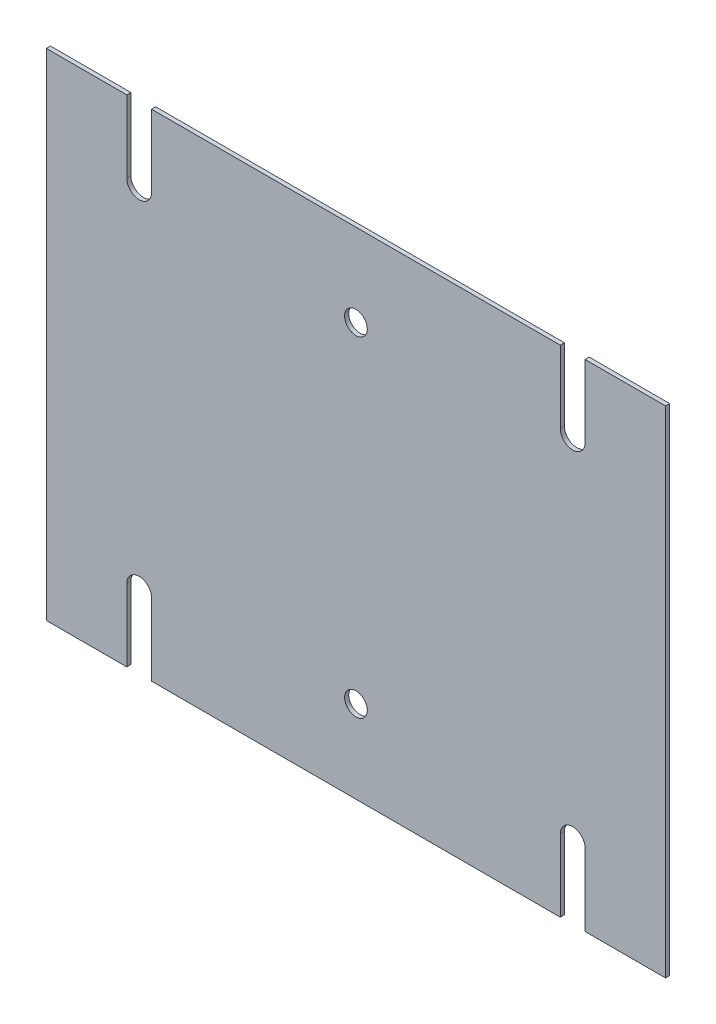
SolidWorks part; units mm, degrees
material "Galvanized Steel"
ref_plane "Front Plane" through (0, 0, 0) normal (0, 0, 1) x (1, 0, 0)
ref_plane "Top Plane" through (0, 0, 0) normal (0, 1, 0) x (1, 0, 0)
ref_plane "Right Plane" through (0, 0, 0) normal (1, 0, 0) x (0, 0, -1)
sketch "Sketch1" plane through (0, 0, 0) normal (0, 0, 1) x (1, 0, 0)
  line L0 (68.9488, -26.6338) -> (98.9488, -26.6338)
  line L1 (68.9488, 58.3662) -> (29.9488, 58.3662)
  line L2 (68.9488, 58.3662) -> (68.9488, -26.6338)
  line L3 (68.9488, -181.6338) -> (29.9488, -181.6338)
  line L4 (-231.0512, 58.3662) -> (-231.0512, -30.1799)
  line L5 (98.9488, -26.6338) -> (98.9488, -96.6338)
  line L6 (98.9488, -96.6338) -> (68.9488, -96.6338)
  line L7 (-231.0512, -30.1799) -> (-261.0512, -30.1799)
  line L8 (-261.0512, -30.1799) -> (-261.0512, -100.1799)
  line L9 (-261.0512, -100.1799) -> (-231.0512, -100.1799)
  line L10 (-231.0512, -100.1799) -> (-231.0512, -181.6338)
  line L11 (68.9488, -96.6338) -> (68.9488, -181.6338)
  line L12 (17.9488, -181.6338) -> (-180.0512, -181.6338)
  line L13 (-180.0512, 58.3662) -> (-180.0512, 23.3662)
  line L14 (-192.0512, 58.3662) -> (-192.0512, 23.3662)
  line L16 (-192.0512, -181.6338) -> (-192.0512, -146.6338)
  line L17 (-180.0512, -181.6338) -> (-180.0512, -146.6338)
  line L18 (-192.0512, -181.6338) -> (-231.0512, -181.6338)
  line L19 (29.9488, -146.6338) -> (29.9488, -181.6338)
  line L20 (17.9488, -146.6338) -> (17.9488, -181.6338)
  line L21 (-192.0512, 58.3662) -> (-231.0512, 58.3662)
  line L22 (29.9488, 58.3662) -> (29.9488, 23.3662)
  line L23 (17.9488, 58.3662) -> (17.9488, 23.3662)
  line L24 (17.9488, 58.3662) -> (-180.0512, 58.3662)
  circle A0 centre (-81.0512, -141.6338) radius 5.5
  arc A1 (-192.0512, 23.3662) -> (-180.0512, 23.3662) centre (-186.0512, 23.3662) ccw
  circle A2 centre (-81.0512, 18.3662) radius 5.5
  arc A3 (-180.0512, -146.6338) -> (-192.0512, -146.6338) centre (-186.0512, -146.6338) ccw
  arc A4 (29.9488, -146.6338) -> (17.9488, -146.6338) centre (23.9488, -146.6338) ccw
  circle A5 centre (83.9488, -61.6338) radius 3.25
  circle A6 centre (-246.0512, -65.1799) radius 3.25
  arc A7 (17.9488, 23.3662) -> (29.9488, 23.3662) centre (23.9488, 23.3662) ccw
  point P14 (-186.0512, 50.7838)
  point P21 (-186.0512, -182.4408)
  point P26 (23.9488, -182.4408)
  point P33 (23.9488, 50.7838)
  dimension "D18" = 11
  dimension "D19" = 11
  dimension "D20" = 6.5
  dimension "D21" = 6.5
  dimension "D26" = 11
  dimension "D27" = 6.5
  dimension "D1" = 240
  dimension "D2" = 300
  dimension "D3" = 30
  dimension "D4" = 70
  dimension "D5" = 45
  dimension "D6" = 30
  dimension "D7" = 70
  dimension "D8" = 12
  dimension "D9" = 12
  dimension "D10" = 39
  dimension "D11" = 39
  dimension "D12" = 12
  dimension "D13" = 12
  dimension "D14" = 35
  dimension "D15" = 35
  dimension "D16" = 35
  dimension "D17" = 35
  dimension "D22" = 150
  dimension "D23" = 40
  dimension "D24" = 150
  dimension "D25" = 40
  dimension "D28" = 15
  dimension "D29" = 35
  dimension "D30" = 15
  dimension "D31" = 35
extrude "Boss-Extrude1" add sketch "Sketch1" along normal blind 2
sketch "Sketch2" plane through (0, 0, 2) normal (0, 0, 1) x (1, 0, 0)
  line L0 (68.9488, -26.6338) -> (68.9488, -96.6338)
  line L1 (68.9488, -96.6338) -> (98.9488, -96.6338)
  line L2 (98.9488, -96.6338) -> (98.9488, -26.6338)
  line L3 (98.9488, -26.6338) -> (68.9488, -26.6338)
extrude "Cut-Extrude1" cut sketch "Sketch2" against normal through all both and the other way through all
sketch "Sketch3" plane through (0, 0, 2) normal (0, 0, 1) x (1, 0, 0)
  line L0 (-231.0512, -30.1799) -> (-231.0512, -100.1799)
  line L1 (-231.0512, -100.1799) -> (-261.0512, -100.1799)
  line L2 (-261.0512, -100.1799) -> (-261.0512, -30.1799)
  line L3 (-261.0512, -30.1799) -> (-231.0512, -30.1799)
extrude "Cut-Extrude2" cut sketch "Sketch3" against normal through all both and the other way through all
